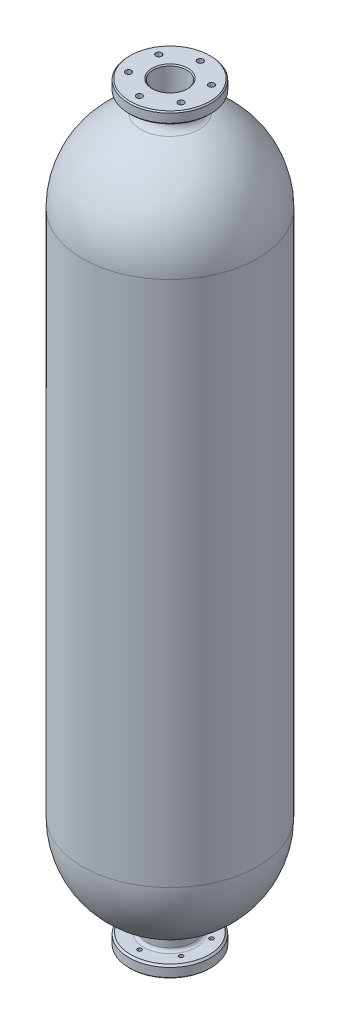
SolidWorks part; units mm, degrees
material "Custom Plastic"
ref_plane "Front Plane" through (0, 0, 0) normal (0, 0, 1) x (1, 0, 0)
ref_plane "Top Plane" through (0, 0, 0) normal (0, 1, 0) x (1, 0, 0)
ref_plane "Right Plane" through (0, 0, 0) normal (1, 0, 0) x (0, 0, -1)
sketch "Sketch2" plane through (0, 0, 0) normal (0, 0, 1) x (1, 0, 0)
  line L0 (0, 415.4698) -> (0, 0) construction
  line L1 (-150, 450.5) -> (-150, -450.5)
  line L2 (-150, 0) -> (141.188, 0) construction
  line L3 (-142, 450.5) -> (-142, -450.5)
  line L6 (0, 642.5) -> (-40, 642.5)
  line L7 (-40, 617.5) -> (-40, 606.0635)
  line L9 (-150, 450.5) -> (-150, -491.4186) construction
  line L10 (-142, 450.5) -> (-142, -489.6108) construction
  line L14 (0, 592.5) -> (0, 642.5)
  line L15 (-40, 642.5) -> (-68, 642.5)
  line L16 (-70, 640.5) -> (-70, 625.5)
  line L17 (-67, 622.5) -> (-45, 622.5)
  line L18 (-70, 625.5) -> (-67, 622.5)
  line L19 (-68, 642.5) -> (-70, 640.5)
  line L32 (-68, -642.5) -> (-70, -640.5)
  line L33 (-70, -625.5) -> (-67, -622.5)
  line L34 (-67, -622.5) -> (-45, -622.5)
  line L35 (-70, -640.5) -> (-70, -625.5)
  line L36 (-40, -642.5) -> (-68, -642.5)
  line L37 (0, -592.5) -> (0, -642.5)
  line L38 (-40, -617.5) -> (-40, -606.0635)
  line L39 (0, -642.5) -> (-40, -642.5)
  arc A0 (-50, 591.9214) -> (-150, 450.5) centre (0, 450.5) ccw
  arc A3 (0, 592.5) -> (-142, 450.5) centre (0, 450.5) ccw
  arc A4 (0, 600.5) -> (-150, 450.5) centre (0, 450.5) ccw construction
  arc A5 (-40, 606.0635) -> (-50, 591.9214) centre (-55, 606.0635) cw
  arc A6 (0, -586.7) -> (-150, -491.4186) centre (0, -420.988) cw construction
  arc A7 (0, -578.7) -> (-142, -489.6108) centre (0, -420.988) cw construction
  arc A8 (0, 592.5) -> (-142, 450.5) centre (0, 450.5) ccw construction
  arc A12 (-45, 622.5) -> (-40, 617.5) centre (-45, 617.5) cw
  arc A17 (-45, -622.5) -> (-40, -617.5) centre (-45, -617.5) ccw
  arc A18 (-40, -606.0635) -> (-50, -591.9214) centre (-55, -606.0635) ccw
  arc A19 (0, -592.5) -> (-142, -450.5) centre (0, -450.5) cw
  arc A20 (-50, -591.9214) -> (-150, -450.5) centre (0, -450.5) cw
  point P23 (-70, 642.5)
  point P28 (-70, -622.5)
  point P34 (-142, 0)
  point P35 (-70, 622.5)
  point P50 (-142, 0)
  point P51 (-142, 0)
  point P52 (-70, -642.5)
  dimension "D3" = 8
  dimension "D1" = 15
  dimension "D9" = 5
  dimension "D2" = 300
  dimension "D4" = 642.5
  dimension "D5" = 50
  dimension "D6" = 40
  dimension "D7" = 20
  dimension "D8" = 70
revolve "Revolve1" add sketch "Sketch2" angle 360 about L0
sketch "Sketch5" plane through (0, 642.5, 0) normal (0, 1, 0) x (1, 0, 0)
  line L0 (0, 0) -> (0, 50) construction
  circle A0 centre (0, 0) radius 50 construction
  point P0 (0, 0)
  dimension "D1" = 100
hole_wizard "3/8 Clearance Hole1" positions "Sketch6" profile "Sketch7" hole size "3/8" standard "ANSI Inch"
sketch "Sketch6" plane through (0, 642.5, 0) normal (0, 1, 0) x (1, 0, 0)
  point P8 (0, 52)
  dimension "D1" = 52
sketch "Sketch7" plane through (0, 642.5, -52) normal (1, 0, 0) x (0, 0, 1)
  line L0 (0, 0) -> (0, 22.0795)
  line L1 (0, 22.0795) -> (5.0419, 19.05)
  line L2 (5.0419, 19.05) -> (5.0419, 0)
  line L5 (5.0419, 0) -> (0, 0)
  line L10 (0, 22.0795) -> (-5.0419, 19.05) construction
  line L11 (0, -6.35) -> (0, 107.95) construction
  dimension "Hole Dia." = 10.0838
  dimension "Hole Depth" = 19.05
  dimension "Drill Angle" = 118
pattern_circular "CirPattern1" count 6 over 360 about axis through (0, 0, 0) along (0, 1, 0) of "3/8 Clearance Hole1"
hole_wizard "2-11-1/2 NPSM Tapped Hole1" positions "Sketch5" profile "Sketch8" tap size "2-11-1/2 NPSM" standard "ANSI Inch"
cosmetic thread "Hole Thread1" parameters "D1"=119.43, "D2"=59.7154
sketch "Sketch8" plane through (0, 642.5, 0) normal (1, 0, 0) x (0, 0, 1)
  line L0 (0, 0) -> (0, 209.2383)
  line L1 (0, 209.2383) -> (28.6893, 192)
  line L2 (28.6893, 192) -> (28.6893, 1.8034)
  line L3 (28.6893, 1.8034) -> (30.4927, 0)
  line L5 (30.4927, 0) -> (0, 0)
  line L6 (-28.6893, 1.8034) -> (-30.4927, 0) construction
  line L10 (0, 209.2383) -> (-28.6893, 192) construction
  line L11 (0, -6.35) -> (0, 107.95) construction
  dimension "Tap Drill Dia." = 57.3786
  dimension "Tap Drill Depth" = 192
  dimension "Near C'Sink Dia." = 60.9854
  dimension "Near C'Sink Angle" = 90
  dimension "Drill Angle" = 118
mirror "Mirror2" about plane through (0, 0, 0) normal (0, 1, 0) of "CirPattern1", "3/8 Clearance Hole1"
mirror "Mirror3" about plane through (0, 0, 0) normal (0, 1, 0) of "2-11-1/2 NPSM Tapped Hole1"
cosmetic thread "Hole Thread2" parameters "D1"=119.43, "D2"=59.7154
